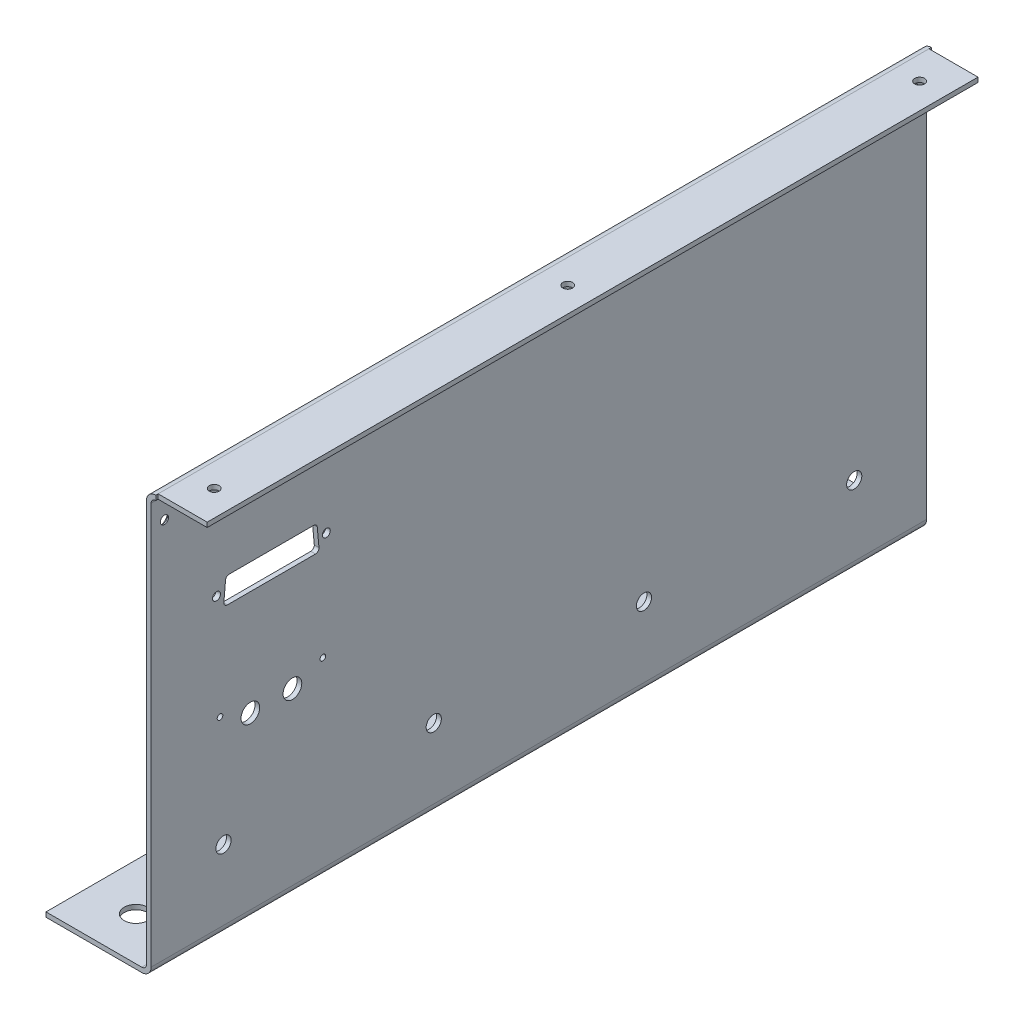
SolidWorks part; units mm, degrees
ref_plane "Спереди" through (0, 0, 0) normal (0, 0, 1) x (1, 0, 0)
ref_plane "Сверху" through (0, 0, 0) normal (0, 1, 0) x (1, 0, 0)
ref_plane "Справа" through (0, 0, 0) normal (1, 0, 0) x (0, 0, -1)
sketch "Эскиз1" plane through (0, 0, 0) normal (0, 0, 1) x (1, 0, 0)
  line L0 (0, 0) -> (0, 82.8028) construction
  line L1 (-1, -68) -> (-1, 104)
  line L4 (1, -68) -> (1, 104)
  line L5 (0, 0) -> (50.6989, 0) construction
  line L6 (3, 106) -> (24, 106)
  line L7 (3, 108) -> (24, 108)
  line L9 (-3, -72) -> (-44, -72)
  line L10 (24, 108) -> (24, 106)
  line L12 (-3, -70) -> (-44, -70)
  line L13 (-44, -72) -> (-44, -70)
  arc A0 (3, 106) -> (1, 104) centre (3, 104) ccw
  arc A1 (-3, -70) -> (-1, -68) centre (-3, -68) ccw
  arc A2 (-3, -72) -> (1, -68) centre (-3, -68) ccw
  arc A3 (-1, 104) -> (3, 108) centre (3, 104) cw
  dimension "D7" = 2
  dimension "D8" = 4
  dimension "D1" = 2
  dimension "D2" = 180
  dimension "D3" = 2
  dimension "D4" = 25
  dimension "D5" = 45
  dimension "D6" = 2
extrude "Вытянуть1" add sketch "Эскиз1" along normal blind 332
sketch "Эскиз2" plane through (-1, 0, 0) normal (-1, 0, 0) x (0, 0, 1)
  line L0 (-8.3976, -38) -> (341.3976, -38) construction
  line L1 (332, -72) -> (0, -72) construction
  line L2 (166, 127.3322) -> (166, -99.1297) construction
  line L3 (0, 104) -> (0, -68) construction
  line L4 (332, 104) -> (332, -68) construction
  circle A0 centre (31, -38) radius 3.25
  circle A1 centre (121, -38) radius 3.25
  circle A2 centre (211, -38) radius 3.25
  circle A3 centre (301, -38) radius 3.25
  dimension "D2" = 90
  dimension "D4" = 6.5
  dimension "D1" = 34
  dimension "D3" = 31
extrude "Вырез-Вытянуть1" cut sketch "Эскиз2" against normal blind 5
sketch "Эскиз3" plane through (0, -70, 0) normal (0, 1, 0) x (1, 0, 0)
  line L0 (-79.1329, -166) -> (76.6618, -166) construction
  line L1 (-24, 28.7881) -> (-24, -351.4381) construction
  line L4 (-44, -332) -> (-44, 0) construction
  line L5 (-3, 0) -> (-44, 0) construction
  line L6 (-3, -332) -> (-44, -332) construction
  circle A0 centre (-24, -18.5) radius 5
  circle A1 centre (-24, -313.5) radius 5
  dimension "D2" = 295
  dimension "D3" = 10
  dimension "D1" = 20
extrude "Вырез-Вытянуть2" cut sketch "Эскиз3" against normal blind 5
sketch "Эскиз4" plane through (0, 108, 0) normal (0, 1, 0) x (1, 0, 0)
  line L0 (-77.123, -166) -> (75.0406, -166) construction
  line L1 (24, 0) -> (3, 0) construction
  line L2 (24, -332) -> (3, -332) construction
  line L3 (3, -332) -> (3, 0) construction
  line L4 (3, -1) -> (29.1791, -1)
  line L5 (3, -1) -> (3, 2.2573)
  line L6 (3, 2.2573) -> (29.1791, 2.2573)
  line L7 (29.1791, -1) -> (29.1791, 2.2573)
  line L8 (24, -332) -> (24, 0) construction
  line L9 (29.1791, -331) -> (29.1791, -334.2573)
  line L10 (3, -334.2573) -> (29.1791, -334.2573)
  line L11 (3, -331) -> (3, -334.2573)
  line L12 (3, -331) -> (29.1791, -331)
  dimension "D1" = 1
  dimension "D2" = 21
extrude "Вырез-Вытянуть3" cut sketch "Эскиз4" against normal blind 10
sketch "Эскиз5" plane through (-1, 0, 0) normal (-1, 0, 0) x (0, 0, 1)
  line L0 (331, 108) -> (1, 108) construction
  line L1 (0, 104) -> (0, -68) construction
  line L2 (166, -112.0097) -> (166, 140.7956) construction
  line L3 (332, 104) -> (332, -68) construction
  circle A0 centre (5.7, 95) radius 1.75
  circle A1 centre (326.3, 95) radius 1.75
  dimension "D1" = 13
  dimension "D3" = 3.5
  dimension "D2" = 5.7
extrude "Вырез-Вытянуть4" cut sketch "Эскиз5" against normal blind 2.5
chamfer "Фаска1" distance 1.5 angle 45 2 edges at (-1, 96.75, 326.3) (-1, 93.25, 5.7)
sketch "Эскиз6" plane through (-1, 0, 0) normal (-1, 0, 0) x (0, 0, 1)
  line L0 (188.0736, 55.5) -> (356.7544, 55.5) construction
  line L1 (260.1487, 51.6358) -> (260.876, 59.6358)
  line L2 (261.6425, 50) -> (299.3575, 50)
  line L3 (332, -70) -> (0, -70) construction
  line L4 (262.3698, 61) -> (298.6302, 61)
  line L5 (254.3104, 10) -> (306.5925, 10) construction
  line L6 (300.8513, 51.6358) -> (300.124, 59.6358)
  line L7 (280.5, 58.5594) -> (280.5, -21.2494) construction
  line L8 (332, 104) -> (332, -68) construction
  circle A0 centre (257, 55.5) radius 1.7
  circle A1 centre (304, 55.5) radius 1.7
  arc A2 (261.6425, 50) -> (260.1487, 51.6358) centre (261.6425, 51.5) cw
  arc A3 (262.3698, 61) -> (260.876, 59.6358) centre (262.3698, 59.5) ccw
  arc A4 (300.124, 59.6358) -> (298.6302, 61) centre (298.6302, 59.5) ccw
  arc A5 (299.3575, 50) -> (300.8513, 51.6358) centre (299.3575, 51.5) ccw
  circle A6 centre (258.5, 10) radius 1.2
  circle A7 centre (302.5, 10) radius 1.2
  circle A8 centre (271.5, 5) radius 4
  circle A9 centre (289.5, 5) radius 4
  point P14 (260, 50)
  point P17 (261, 61)
  point P20 (300, 61)
  point P23 (301, 50)
  dimension "D4" = 47
  dimension "D5" = 3.4
  dimension "D6" = 1.5
  dimension "D9" = 2.4
  dimension "D11" = 18
  dimension "D12" = 8
  dimension "D13" = 44
  dimension "D14" = 5
  dimension "D1" = 39
  dimension "D2" = 41
  dimension "D3" = 11
  dimension "D7" = 120
  dimension "D8" = 51.5
  dimension "D10" = 40
extrude "Вырез-Вытянуть5" cut sketch "Эскиз6" against normal blind 10
cosmetic thread "Условное изображение резьбы1"
cosmetic thread "Условное изображение резьбы2"
sketch "Эскиз7" plane through (0, 108, 0) normal (0, 1, 0) x (1, 0, 0)
  line L0 (13, 25.443) -> (13, -349.3158) construction
  line L1 (-72.7281, -166) -> (99.4348, -166) construction
  line L2 (-3, 0) -> (-44, 0) construction
  line L3 (-3, -332) -> (-44, -332) construction
  line L4 (24, -331) -> (24, -1) construction
  circle A0 centre (13.3533, -166) radius 2.1
  circle A1 centre (13, -15) radius 2.1
  circle A2 centre (13, -317) radius 2.1
  dimension "D3" = 4.2
  dimension "D1" = 11
  dimension "D2" = 15
extrude "Вырез-Вытянуть6" cut sketch "Эскиз7" against normal blind 10
cosmetic thread "Условное изображение резьбы3"
cosmetic thread "Условное изображение резьбы4"
cosmetic thread "Условное изображение резьбы5"
